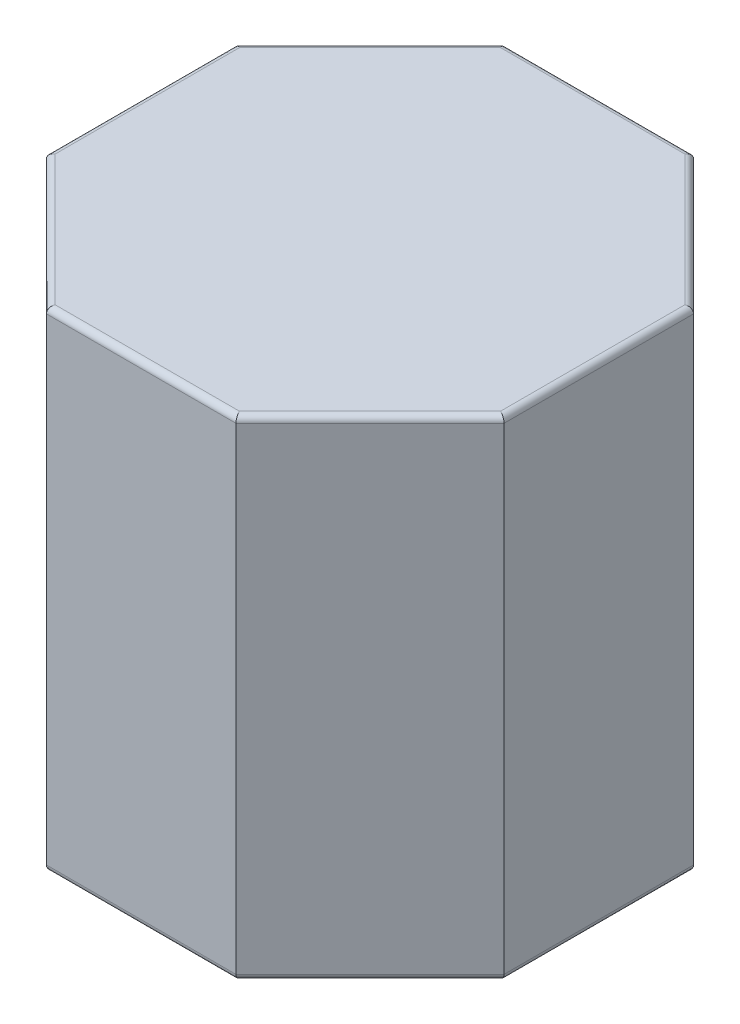
SolidWorks part; units mm, degrees
ref_plane "Front Plane" through (0, 0, 0) normal (1, 0, 0) x (0, 1, 0)
ref_plane "Top Plane" through (0, 0, 0) normal (0, 0, 1) x (0, 1, 0)
ref_plane "Right Plane" through (0, 0, 0) normal (0, 1, 0) x (-1, 0, 0)
sketch "Sketch1" plane through (0, 0, 0) normal (0, 1, 0) x (-1, 0, 0)
  line L0 (7.7455, -18.7006) -> (-7.7461, -18.7006)
  line L1 (-7.7461, -18.7006) -> (-18.7003, -7.7464)
  line L2 (-18.7003, -7.7464) -> (-18.7003, 7.7451)
  line L3 (-18.7003, 7.7451) -> (-7.7461, 18.6994)
  line L4 (-7.7461, 18.6994) -> (7.7455, 18.6994)
  line L5 (7.7455, 18.6994) -> (18.6997, 7.7451)
  line L6 (18.6997, 7.7451) -> (18.6997, -7.7464)
  line L7 (18.6997, -7.7464) -> (7.7455, -18.7006)
extrude "Boss-Extrude1" add sketch "Sketch1" along normal blind 40
fillet "Fillet1" radius 0.5 16 edges at (-13.2226, 0, -13.2235) (-18.6997, 0, -0.0006) (-13.2226, 0, 13.2222) (0.0003, 0, 18.6994) (13.2232, 0, 13.2222) (18.7003, 0, -0.0006) (13.2232, 0, -13.2235) (0.0003, 0, -18.7006) (-13.2226, 40, -13.2235) (-18.6997, 40, -0.0006) (-13.2226, 40, 13.2222) (0.0003, 40, 18.6994) (13.2232, 40, 13.2222) (18.7003, 40, -0.0006) (13.2232, 40, -13.2235) (0.0003, 40, -18.7006)
